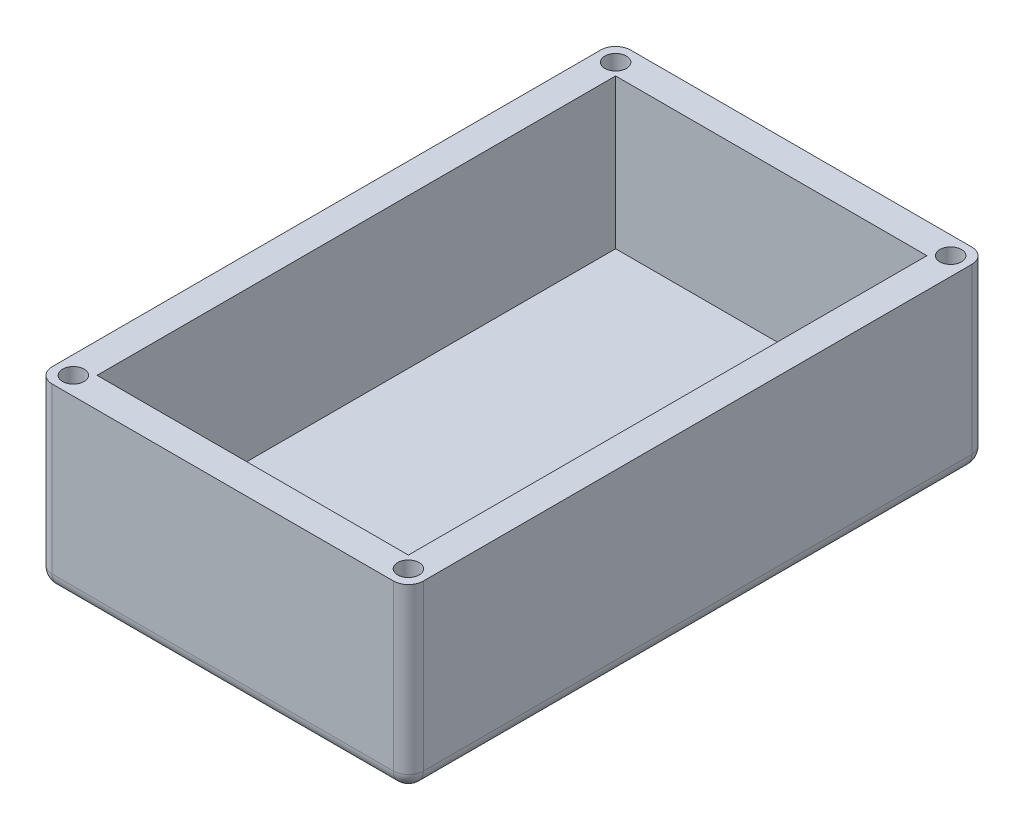
SolidWorks part; units mm, degrees
ref_plane "Front" through (0, 0, 0) normal (0, 0, 1) x (1, 0, 0)
ref_plane "Top" through (0, 0, 0) normal (0, 1, 0) x (1, 0, 0)
ref_plane "Right" through (0, 0, 0) normal (1, 0, 0) x (0, 0, -1)
sketch "Sketch1" plane through (0, 0, 0) normal (0, 1, 0) x (1, 0, 0)
  line L0 (-16.51, 27.5) -> (16.51, -27.5) construction
  line L1 (-16.51, -27.5) -> (16.51, -27.5)
  line L2 (-16.51, -27.5) -> (-16.51, 27.5)
  line L3 (-16.51, 27.5) -> (16.51, 27.5)
  line L4 (16.51, -27.5) -> (16.51, 27.5)
  point P6 (0, 0)
  dimension "D1" = 55
  dimension "D2" = 33.02
extrude "Base" add sketch "Sketch1" along normal blind 3.175 contours L1 L4 L3 L2 | L3 L0 L4
sketch "Sketch3" plane through (0, 0, 0) normal (0, -1, 0) x (1, 0, 0)
  line L7 (-19.685, -30.675) -> (19.685, -30.675)
  line L8 (19.685, 30.675) -> (-19.685, 30.675)
  line L9 (-19.685, 30.675) -> (-19.685, -30.675)
  line L10 (-19.685, -30.675) -> (19.685, -30.675)
  line L11 (-16.51, -27.5) -> (16.51, -27.5)
  line L12 (19.685, 30.675) -> (-19.685, 30.675)
  line L13 (-19.685, 30.675) -> (-19.685, -30.675)
  line L14 (-16.51, -27.5) -> (16.51, -27.5)
  line L16 (16.51, 27.5) -> (-16.51, 27.5)
  line L17 (-16.51, 27.5) -> (-16.51, -27.5)
  line L18 (19.685, -30.675) -> (19.685, 30.675)
  line L19 (19.685, -30.675) -> (19.685, 30.675)
  line L20 (16.51, 27.5) -> (-16.51, 27.5)
  line L21 (-16.51, 27.5) -> (-16.51, -27.5)
  line L22 (16.51, -27.5) -> (16.51, 27.5)
  line L23 (16.51, -27.5) -> (16.51, 27.5)
  dimension "D1" = 3.175
  dimension "D2" = 0
extrude "Outer-Casing" add sketch "Sketch3" against normal blind 19.05
fillet "Fillet1" radius 1.5875 8 edges at (0, 0, -30.675) (-19.685, 0, 0) (0, 0, 30.675) (19.685, 0, 0) (19.685, 9.525, 30.675) (19.685, 9.525, -30.675) (-19.685, 9.525, -30.675) (-19.685, 9.525, 30.675)
sketch "Sketch5" plane through (0, 19.05, 0) normal (0, 1, 0) x (1, 0, 0)
  line L0 (-19.22, 30.21) -> (-16.51, 27.5) construction
  line L1 (0, 30.675) -> (0, -30.675) construction
  line L2 (-18.0975, 30.675) -> (18.0975, 30.675) construction
  line L3 (18.0975, -30.675) -> (-18.0975, -30.675) construction
  line L5 (-19.685, -29.0875) -> (-19.685, 29.0875) construction
  line L6 (-19.685, 0) -> (19.685, 0) construction
  line L7 (19.685, 29.0875) -> (19.685, -29.0875) construction
  circle A0 centre (-17.7672, 28.7572) radius 1.143
  circle A1 centre (-17.7672, -28.7572) radius 1.143
  circle A2 centre (17.7672, 28.7572) radius 1.143
  circle A3 centre (17.7672, -28.7572) radius 1.143
  arc A4 (-18.0975, 30.675) -> (-19.685, 29.0875) centre (-18.0975, 29.0875) ccw construction
  dimension "D1" = 2.286
  dimension "D2" = 1.778
extrude "Cut-Extrude5" cut sketch "Sketch5" against normal blind 6.35 contours A0 | A1 | A3 | A2
